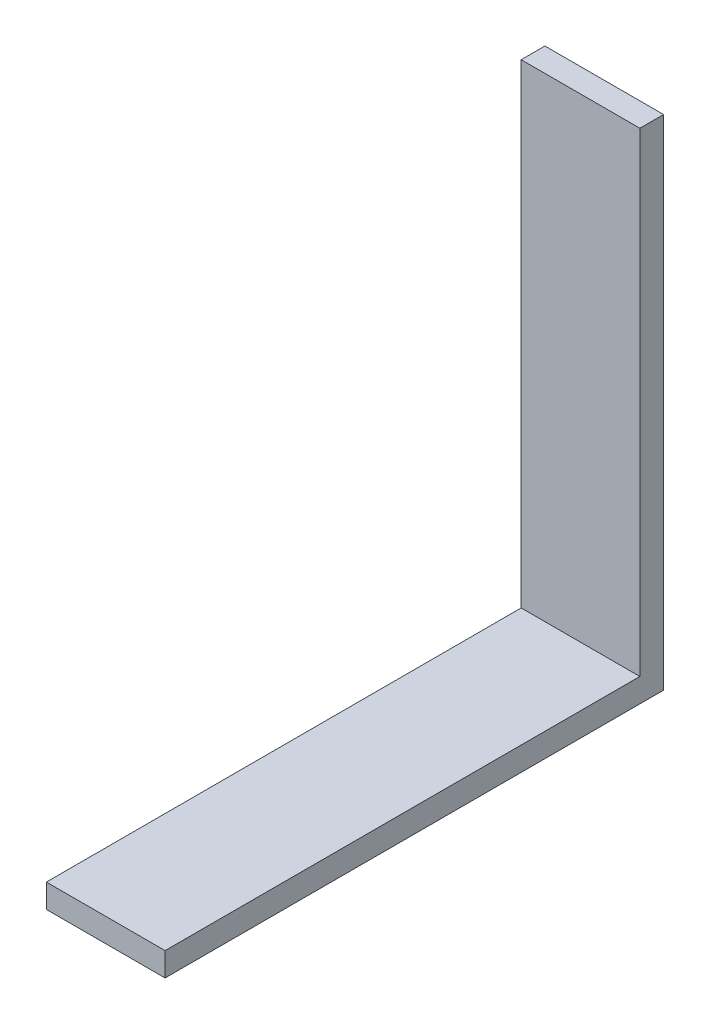
SolidWorks part; units mm, degrees
ref_plane "Front Plane" through (0, 0, 0) normal (0, 0, 1) x (1, 0, 0)
ref_plane "Top Plane" through (0, 0, 0) normal (0, 1, 0) x (1, 0, 0)
ref_plane "Right Plane" through (0, 0, 0) normal (1, 0, 0) x (0, 0, -1)
sketch "Sketch1" plane through (0, 0, 0) normal (1, 0, 0) x (0, 0, -1)
  line L0 (-42, 0) -> (0, 0)
  line L1 (55, 0) -> (-55, 0) construction
  line L2 (0, 0) -> (0, 42)
  line L3 (0, 44.2539) -> (0, -44.2539) construction
  line L4 (0, 42) -> (-2, 42)
  line L5 (-2, 42) -> (-2, 2)
  line L6 (-2, 2) -> (-42, 2)
  line L7 (-42, 2) -> (-42, 0)
  dimension "D1" = 40
  dimension "D2" = 2
extrude "Boss-Extrude1" add sketch "Sketch1" along normal mid plane 10
